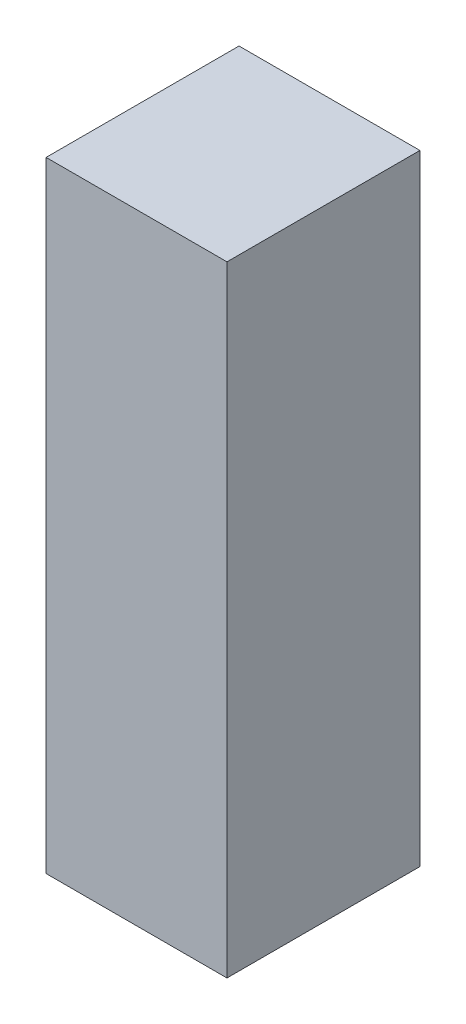
SolidWorks part; units mm, degrees
ref_plane "Front Plane" through (0, 0, 0) normal (0, 0, 1) x (1, 0, 0)
ref_plane "Top Plane" through (0, 0, 0) normal (0, 1, 0) x (1, 0, 0)
ref_plane "Right Plane" through (0, 0, 0) normal (1, 0, 0) x (0, 0, -1)
sketch "Sketch1" plane through (0, 0, 0) normal (0, 1, 0) x (1, 0, 0)
  line L1 (15, -16) -> (-15, -16)
  line L2 (15, -16) -> (15, 16)
  line L3 (15, 16) -> (-15, 16)
  line L4 (-15, -16) -> (-15, 16)
  line L5 (15, -16) -> (-15, 16) construction
  line L6 (15, 16) -> (-15, -16) construction
  point P0 (0, 0)
  dimension "D1" = 32
  dimension "D2" = 30
extrude "Boss-Extrude1" add sketch "Sketch1" along normal blind 102.87
